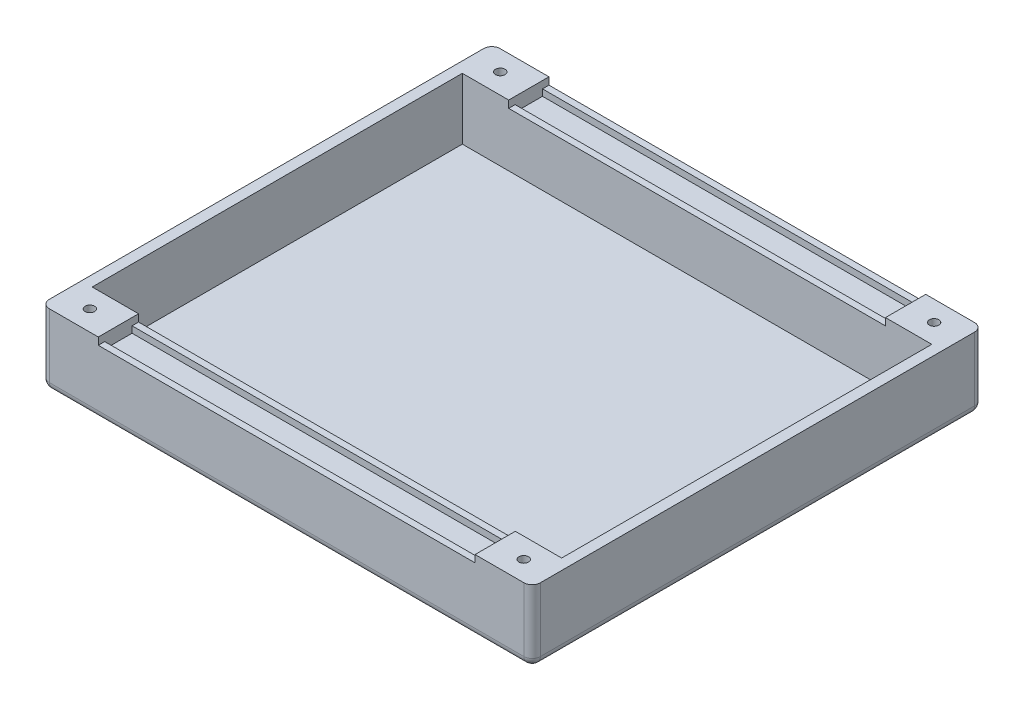
SolidWorks part; units mm, degrees
ref_plane "Front Plane" through (0, 0, 0) normal (0, 0, 1) x (1, 0, 0)
ref_plane "Top Plane" through (0, 0, 0) normal (0, 1, 0) x (1, 0, 0)
ref_plane "Right Plane" through (0, 0, 0) normal (1, 0, 0) x (0, 0, -1)
sketch "Sketch1" plane through (0, 0, 0) normal (0, 1, 0) x (1, 0, 0)
  line L1 (-114.02, -104.66) -> (114.02, -104.66)
  line L2 (-114.02, -104.66) -> (-114.02, 104.66)
  line L3 (-114.02, 104.66) -> (114.02, 104.66)
  line L4 (114.02, -104.66) -> (114.02, 104.66)
  line L5 (-114.02, -104.66) -> (114.02, 104.66) construction
  line L6 (-114.02, 104.66) -> (114.02, -104.66) construction
  point P0 (0, 0)
  dimension "D1" = 228.04
  dimension "D2" = 209.32
extrude "Boss-Extrude1" add sketch "Sketch1" along normal blind 33.5
sketch "Sketch2" plane through (0, 33.5, 0) normal (0, 1, 0) x (1, 0, 0)
  line L1 (-109.02, -85.96) -> (109.02, -85.96)
  line L2 (-109.02, -85.96) -> (-109.02, 85.96)
  line L3 (-109.02, 85.96) -> (109.02, 85.96)
  line L4 (109.02, -85.96) -> (109.02, 85.96)
  line L5 (-109.02, -85.96) -> (109.02, 85.96) construction
  line L6 (-109.02, 85.96) -> (109.02, -85.96) construction
  point P0 (0, 0)
  dimension "D1" = 218.04
  dimension "D2" = 171.92
extrude "Cut-Extrude1" cut sketch "Sketch2" against normal blind 28.5
sketch "Sketch4" plane through (0, 33.5, 0) normal (0, 1, 0) x (1, 0, 0)
  line L0 (-109.02, -85.96) -> (109.02, -85.96) construction
  line L1 (-87.5, -85.96) -> (87.5, -85.96)
  line L2 (-87.5, -85.96) -> (-87.5, -104.66)
  line L3 (-87.5, -104.66) -> (87.5, -104.66)
  line L4 (87.5, -85.96) -> (87.5, -104.66)
  line L5 (-114.02, -104.66) -> (114.02, -104.66) construction
  point P4 (0, -85.96)
  dimension "D1" = 175
extrude "Cut-Extrude2" cut sketch "Sketch4" against normal blind 3.35
sketch "Sketch5" plane through (0, 30.15, 0) normal (0, 1, 0) x (1, 0, 0)
  line L1 (-87.5, -88.96) -> (87.5, -88.96)
  line L2 (-87.5, -88.96) -> (-87.5, -101.66)
  line L3 (-87.5, -101.66) -> (87.5, -101.66)
  line L4 (87.5, -88.96) -> (87.5, -101.66)
  line L5 (-87.5, -85.96) -> (-87.5, -104.66) construction
  point P4 (-87.5, -95.31)
  dimension "D1" = 12.7
  dimension "D2" = 175
extrude "Cut-Extrude3" cut sketch "Sketch5" against normal blind 3
sketch "Sketch6" plane through (0, 33.5, 0) normal (0, 1, 0) x (1, 0, 0)
  line L0 (109.02, 85.96) -> (-109.02, 85.96) construction
  line L1 (-87.5, 104.66) -> (87.5, 104.66)
  line L2 (-87.5, 104.66) -> (-87.5, 85.96)
  line L3 (-87.5, 85.96) -> (87.5, 85.96)
  line L4 (87.5, 104.66) -> (87.5, 85.96)
  point P4 (0, 85.96)
  dimension "D1" = 175
  dimension "D2" = 18.7
extrude "Cut-Extrude4" cut sketch "Sketch6" against normal blind 3.35
sketch "Sketch7" plane through (0, 30.15, 0) normal (0, 1, 0) x (1, 0, 0)
  line L0 (-87.5, 104.66) -> (-87.5, 85.96) construction
  line L1 (-87.5, 101.66) -> (87.5, 101.66)
  line L2 (-87.5, 101.66) -> (-87.5, 88.96)
  line L3 (-87.5, 88.96) -> (87.5, 88.96)
  line L4 (87.5, 101.66) -> (87.5, 88.96)
  point P4 (-87.5, 95.31)
  dimension "D1" = 12.7
  dimension "D2" = 175
extrude "Cut-Extrude5" cut sketch "Sketch7" against normal blind 3
ref_plane "Plane1" through (0, 0, -35.96) normal (0, 0, 1) x (1, 0, 0)
ref_plane "Plane2" through (0, 0, -52.33) normal (0, 0, 1) x (1, 0, 0)
ref_plane "Plane3" through (0, 0, 0) normal (0, 0, 1) x (1, 0, 0)
sketch "Sketch11" plane through (0, 33.5, 0) normal (0, 1, 0) x (1, 0, 0)
  line L0 (114.02, 104.66) -> (87.5, 104.66) construction
  line L1 (87.5, 85.96) -> (87.5, 104.66) construction
  line L8 (-15.675, 0) -> (15.675, 0) construction
  circle A2 centre (100.76, 95.31) radius 2.2
  circle A3 centre (100.76, -95.31) radius 2.2
  point P1 (110.31, 95.31)
  point P4 (100.76, 104.66)
  point P7 (87.5, 95.31)
  point P9 (0, 0)
  point P10 (101.138, 95.31)
  point P11 (0, 0)
  point P12 (100.76, 95.31)
  point P15 (0, 0)
  dimension "D1" = 4.4
extrude "Cut-Extrude6" cut sketch "Sketch11" against normal blind 33.5
fillet "Fillet3" radius 3.81 8 edges at (-114.02, 16.75, 104.66) (0, 0, 104.66) (114.02, 16.75, 104.66) (114.02, 0, 0) (114.02, 16.75, -104.66) (0, 0, -104.66) (-114.02, 16.75, -104.66) (-114.02, 0, 0)
ref_plane "Plane4" through (0, 0, 0) normal (-1, 0, 0) x (0, 0, 1)
mirror "Mirror1" about plane through (0, 0, 0) normal (-1, 0, 0) of "Cut-Extrude6"
